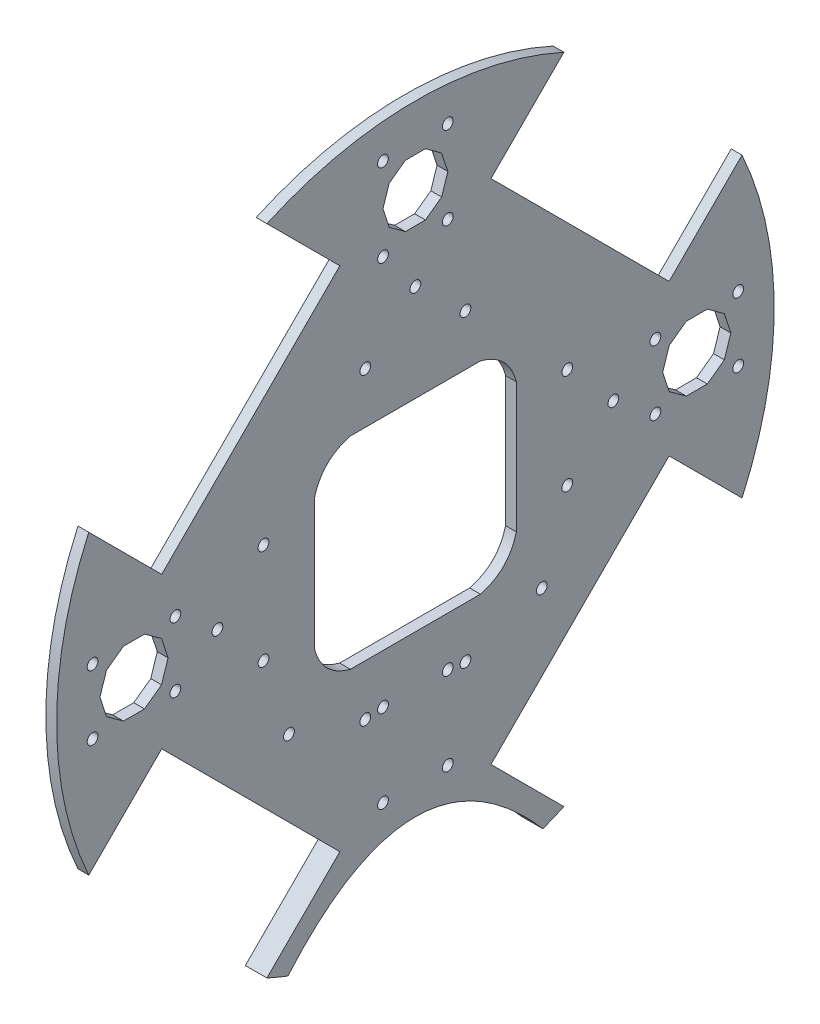
SolidWorks part; units mm, degrees
ref_plane "Front Plane" through (0, 0, 0) normal (0, 0, 1) x (1, 0, 0)
ref_plane "Top Plane" through (0, 0, 0) normal (0, 1, 0) x (1, 0, 0)
ref_plane "Right Plane" through (0, 0, 0) normal (1, 0, 0) x (0, 0, -1)
sketch "Sketch1" plane through (0, 0, 0) normal (1, 0, 0) x (0, 0, -1)
  line L7 (-70.4875, 70.4875) -> (-45.7388, 95.2363)
  line L21 (-70.4875, 70.4875) -> (-95.2363, 45.7388)
  line L23 (-95.2363, 45.7388) -> (-70.4875, 20.9901)
  line L24 (-70.4875, 20.9901) -> (-20.9901, 70.4875)
  line L25 (-20.9901, 70.4875) -> (-45.7388, 95.2363)
  line L26 (70.4875, -70.4875) -> (45.7388, -95.2363)
  line L28 (95.2363, -45.7388) -> (70.4852, -20.9878)
  line L29 (70.4852, -20.9878) -> (19.2145, -68.712)
  line L30 (19.2145, -68.712) -> (45.7388, -95.2363)
  line L31 (70.4875, -70.4875) -> (95.2363, -45.7388)
  line L32 (70.4875, 70.4875) -> (45.7388, 95.2363)
  line L33 (45.7388, 95.2363) -> (95.2363, 45.7388)
  line L34 (95.2363, 45.7388) -> (70.4852, 20.9878)
  line L35 (70.4852, 20.9878) -> (20.9855, 70.4875)
  line L36 (20.9855, 70.4875) -> (45.7388, 95.2363)
  line L37 (-70.4875, -70.4875) -> (-45.7388, -95.2363)
  line L38 (-45.7388, -95.2363) -> (-20.9901, -70.4875)
  line L39 (-20.9901, -70.4875) -> (-70.4875, -20.9901)
  line L40 (-70.4875, -20.9901) -> (-95.2363, -45.7388)
  line L41 (-95.2363, -45.7388) -> (-70.4875, -70.4875)
  circle A0 centre (0, 0) radius 99.6844
  spline S0 degree 2 poles (-29.4455, -95.2363) (0, -54.1326) (29.4455, -95.2363) knots 0 0 0 1 1 1
extrude "Boss-Extrude5" add sketch "Sketch1" along normal blind 3 contours A0 S0 L30 L29 L28 L34 L35 L36 L25 L24 L23 L40 L39 L38
sketch "Sketch5" plane through (3, 0, 0) normal (1, 0, 0) x (0, 0, -1)
  line L0 (0, 0) -> (0, -55)
  line L1 (43.3013, 0) -> (21.6506, 37.5)
  line L2 (21.6506, 37.5) -> (-21.6506, 37.5)
  line L3 (-21.6506, 37.5) -> (-43.3013, 0)
  line L4 (-43.3013, 0) -> (-21.6506, -37.5)
  line L5 (-21.6506, -37.5) -> (21.6506, -37.5)
  line L6 (21.6506, -37.5) -> (43.3013, 0)
  line L7 (0, 0) -> (55, 0)
  line L8 (55, 0) -> (0, 0)
  line L9 (0, 0) -> (0, 55)
  line L10 (0, 55) -> (0, 0)
  line L11 (0, 0) -> (-55, 0)
  circle A0 centre (0, 0) radius 37.5 construction
  circle A1 centre (0, 55) radius 1.5
  circle A2 centre (55, 0) radius 1.5
  circle A3 centre (0, -55) radius 1.5
  circle A4 centre (-55, 0) radius 1.5
extrude "Cut-Extrude2" cut sketch "Sketch5" against normal blind 3
sketch "Sketch6" plane through (3, 0, 0) normal (1, 0, 0) x (0, 0, -1)
  line L16 (41.2207, 8.9998) -> (41.2207, 8.999)
  circle A3 centre (-9.0093, 89.6878) radius 1.5
  circle A4 centre (8.9907, 89.6878) radius 1.5
  circle A5 centre (8.9907, 66.6878) radius 1.5
  circle A6 centre (-9.0093, 66.6878) radius 1.5
  circle A7 centre (-89.6848, 8.9998) radius 1.5
  circle A8 centre (-66.6848, 8.9998) radius 1.5
  circle A9 centre (-66.6848, -8.998) radius 1.5
  circle A10 centre (-89.6848, -8.998) radius 1.5
  circle A11 centre (9, -41.6844) radius 1.5
  circle A12 centre (-9, -41.6844) radius 1.5
  circle A13 centre (-9, -64.6844) radius 1.5
  circle A14 centre (9, -64.6844) radius 1.5
  circle A15 centre (66.6778, 9.0051) radius 1.5
  circle A16 centre (89.6778, 9.0051) radius 1.5
  circle A17 centre (89.6778, -8.9928) radius 1.5
  circle A18 centre (66.6778, -8.9928) radius 1.5
extrude "Cut-Extrude3" cut sketch "Sketch6" against normal blind 3 contours A7 | A8 | A10 | A9 | A4 | A3 | A6 | A5 | A15 | A16 | A17 | A18 | A11 | A12 | A13 | A14
sketch "Sketch7" plane through (3, 0, 0) normal (1, 0, 0) x (0, 0, -1)
  line L2 (21.6506, -37.5) -> (43.3013, 0)
  line L3 (43.3013, 0) -> (21.6506, 37.5)
  line L4 (21.6506, 37.5) -> (-21.6506, 37.5)
  line L5 (-21.6506, 37.5) -> (-43.3013, 0)
  line L6 (-43.3013, 0) -> (-21.6506, -37.5)
  line L7 (-21.6506, -37.5) -> (21.6506, -37.5)
  circle A0 centre (0, 0) radius 37.5 construction
extrude "Boss-Extrude7" add sketch "Sketch7" against normal blind 3 contours L2 L3 L4 L5 L6 L7
sketch "Sketch8" plane through (3, 0, 0) normal (1, 0, 0) x (0, 0, -1)
  circle A0 centre (-49.2746, 20.989) radius 1.5
  circle A1 centre (-20.99, 49.2744) radius 1.5
  circle A2 centre (20.9866, 49.2729) radius 1.5
  circle A3 centre (49.2712, 20.989) radius 1.5
  circle A4 centre (49.2692, -20.2436) radius 1.5
  circle A5 centre (19.9904, -47.4971) radius 1.5
  circle A6 centre (-20.99, -49.274) radius 1.5
  circle A7 centre (-49.2746, -20.9901) radius 1.5
extrude "Cut-Extrude4" cut sketch "Sketch8" against normal blind 3
sketch "Sketch9" plane through (3, 0, 0) normal (1, 0, 0) x (0, 0, -1)
  line L12 (32.6284, 7.0711) -> (7.0711, 32.6284)
  line L13 (-7.0711, 32.6284) -> (-32.6284, 7.0711)
  line L14 (-32.6284, -7.0711) -> (-7.0711, -32.6284)
  line L15 (7.0711, -32.6284) -> (32.6284, -7.0711)
  circle A0 centre (0, 0) radius 28.0718 construction
  arc A1 (-7.0711, -32.6284) -> (7.0711, -32.6284) centre (0, -25.5574) ccw
  arc A2 (32.6284, -7.0711) -> (32.6284, 7.0711) centre (25.5574, 0) ccw
  arc A3 (7.0711, 32.6284) -> (-7.0711, 32.6284) centre (0, 25.5574) ccw
  arc A4 (-32.6284, 7.0711) -> (-32.6284, -7.0711) centre (-25.5574, 0) ccw
  dimension "D1" = 10
extrude "Cut-Extrude5" cut sketch "Sketch9" against normal blind 3 contours L12 A3 L13 A4 L14 A1 L15 A2
sketch "Sketch10" plane through (3, 0, 0) normal (1, 0, 0) x (0, 0, -1)
  line L0 (0, 35.5574) -> (0, -35.5574) construction
  line L1 (4, 35.5574) -> (4, -35.5574)
  line L2 (-4, 35.5574) -> (-4, -35.5574)
  line L3 (-37.5957, 0) -> (35.5574, 0) construction
  line L4 (-37.5957, 4) -> (35.5574, 4)
  line L5 (-37.5957, -4) -> (35.5574, -4)
  arc A0 (7.0711, 32.6284) -> (-7.0711, 32.6284) centre (0, 25.5574) ccw construction
  arc A1 (-7.0711, -32.6284) -> (7.0711, -32.6284) centre (0, -25.5574) ccw construction
  arc A2 (4, 35.5574) -> (-4, 35.5574) centre (0, 35.5574) ccw
  arc A3 (-4, -35.5574) -> (4, -35.5574) centre (0, -35.5574) ccw
  arc A4 (32.6284, -7.0711) -> (32.6284, 7.0711) centre (25.5574, 0) ccw construction
  arc A5 (-37.5957, 4) -> (-37.5957, -4) centre (-37.5957, 0) ccw
  arc A6 (35.5574, -4) -> (35.5574, 4) centre (35.5574, 0) ccw
  point P8 (0, 0)
  point P13 (-1.0192, 0)
extrude "Boss-Extrude9" add sketch "Sketch10" against normal blind 3 contours L4 A5 L5 L2 | L5 A6 L4 L1 | L1 A2 L2 L4 | L2 A3 L1 L5 | L2 L5 L1 L4
sketch "Sketch11" plane through (3, 0, 0) normal (1, 0, 0) x (0, 0, -1)
  circle A0 centre (0, -55) radius 4.2568
extrude "Boss-Extrude10" add sketch "Sketch11" against normal blind 3
sketch "Sketch12" plane through (3, 0, 0) normal (1, 0, 0) x (0, 0, -1)
  line L0 (0, 0) -> (0, -55)
  circle A2 centre (0, -55) radius 5
extrude "Cut-Extrude6" cut sketch "Sketch12" against normal blind 2
sketch "Sketch13" plane through (3, 0, 0) normal (1, 0, 0) x (0, 0, -1)
  line L0 (0, 0) -> (0, -55)
  circle A0 centre (0, -55) radius 1.5
extrude "Cut-Extrude10" cut sketch "Sketch13" against normal blind 10
sketch "Sketch14" plane through (3, 0, 0) normal (1, 0, 0) x (0, 0, -1)
  line L0 (-4, 34.7225) -> (4, 34.7225)
  line L1 (4, 34.7225) -> (4, 4)
  line L2 (4, 4) -> (34.7225, 4)
  line L3 (34.7225, 4) -> (34.7225, -4)
  line L4 (34.7225, -4) -> (4, -4)
  line L5 (4, -4) -> (4, -34.7225)
  line L6 (4, -34.7225) -> (-4, -34.7225)
  line L7 (-4, -34.7225) -> (-4, -4)
  line L8 (-4, -4) -> (-34.7225, -4)
  line L9 (-34.7225, -4) -> (-34.7225, 4)
  line L10 (-34.7225, 4) -> (-4, 4)
  line L11 (-4, 4) -> (-4, 34.7225)
extrude "Cut-Extrude11" cut sketch "Sketch14" against normal blind 10 contours L11 L0 L1 L2 L3 L4 L5 L6 L7 L8 L9 L10
sketch "Sketch15" plane through (3, 0, 0) normal (1, 0, 0) x (0, 0, -1)
  line L0 (-29.4455, -95.2363) -> (-35.4195, -93.1796)
  line L1 (-20.9901, -70.4875) -> (20.9901, -70.4875)
  line L2 (19.2145, -68.712) -> (41.2512, -90.7487) construction
  line L3 (90.7487, -41.2512) -> (70.4852, -20.9878)
  line L4 (70.4852, -20.9878) -> (20.9901, -70.4875)
  line L5 (20.9901, -70.4875) -> (19.2145, -68.712)
  line L6 (19.2145, -68.712) -> (70.4852, -20.9878)
  arc A0 (-41.2512, -90.7487) -> (-29.4455, -95.2363) centre (0, 0) ccw construction
extrude "Boss-Extrude11" add sketch "Sketch15" against normal blind 3 contours L6 L5 L4
sketch "Sketch16" plane through (3, 0, 0) normal (1, 0, 0) x (0, 0, -1)
  line L0 (-20.9901, -70.4875) -> (20.9901, -70.4875)
  line L1 (0, -70.4875) -> (0, -74.6844)
  line L2 (-35.4195, -93.1796) -> (-29.4455, -95.2363)
  line L3 (29.4455, -95.2363) -> (35.4195, -93.1796)
  line L4 (-35.4195, -93.1796) -> (-36.1047, -94.1619)
  line L5 (-36.1047, -94.1619) -> (-29.2458, -96.6155)
  line L6 (-29.2458, -96.6155) -> (-29.4455, -95.2363)
  line L7 (29.4455, -95.2363) -> (26.5031, -98.1787)
  line L8 (26.5031, -98.1787) -> (37.9172, -96.526)
  line L9 (37.9172, -96.526) -> (35.4195, -93.1796)
  arc A0 (-41.2512, -90.7487) -> (-29.4455, -95.2363) centre (0, 0) ccw construction
  arc A1 (29.4455, -95.2363) -> (41.2512, -90.7487) centre (0, 0) ccw construction
  parabola Q0 (-29.4455, -95.2363) -> (29.4455, -95.2363) focus (0, -85.2314) apex (0, -74.6844) construction
  parabola Q1 (-29.4455, -95.2363) -> (29.4455, -95.2363) focus (0, -85.2314) apex (0, -74.6844) construction
  spline S0 degree 2 poles (-35.4195, -93.1796) (0, -51.9923) (35.4195, -93.1796) knots 0 0 0 1 1 1
  spline S1 degree 2 poles (-29.4455, -95.2363) (0, -54.1326) (29.4455, -95.2363) knots 0 0 0 1 1 1
extrude "Cut-Extrude13" cut sketch "Sketch16" against normal blind 3 contours L8 L9 L3 L7 | L1 S1 L3 S0 | L2 S1 L1 S0 | L5 L6 L2 L4
sketch "Sketch17" plane through (3, 0, 0) normal (1, 0, 0) x (0, 0, -1)
  line L0 (-41.2512, -90.7487) -> (-20.9901, -70.4875)
  line L1 (-20.9901, -70.4875) -> (20.9901, -70.4875)
  line L2 (20.9901, -70.4875) -> (41.2512, -90.7487)
  line L3 (41.2512, -90.7487) -> (35.4195, -93.1796)
  line L4 (-41.2512, -90.7487) -> (-35.4195, -93.1796)
  parabola Q0 (-35.4195, -93.1796) -> (35.4195, -93.1796) focus (0, -87.8157) apex (0, -72.586) construction
  spline S0 degree 2 poles (-35.4195, -93.1796) (0, -51.9923) (35.4195, -93.1796) knots 0 0 0 1 1 1
extrude "Boss-Extrude13" add sketch "Sketch17" against normal blind 6 contours S0 L3 L2 L1 L0 L4
sketch "Sketch19" plane through (-3, 0, 0) normal (-1, 0, 0) x (0, 0, 1)
  line L0 (-49.2692, -20.2436) -> (-52.8047, -23.7791)
  line L1 (-49.2712, 20.989) -> (-52.8067, 24.5245)
  line L2 (-19.9904, -47.4971) -> (-23.526, -51.0326)
  line L3 (20.99, -49.274) -> (24.5255, -52.8095)
  line L4 (49.2746, -20.9901) -> (52.8102, -24.5256)
  line L5 (49.2746, 20.989) -> (52.8102, 24.5245)
  line L6 (20.99, 49.2744) -> (24.5255, 52.8099)
  line L7 (-20.9866, 49.2729) -> (-24.5236, 52.8099)
  circle A0 centre (-52.8067, 24.5245) radius 1.5
  circle A1 centre (-24.5236, 52.8099) radius 1.5
  circle A2 centre (24.5255, 52.8099) radius 1.5
  circle A3 centre (52.788, 24.5204) radius 1.5
  circle A4 centre (52.8102, -24.5256) radius 1.5
  circle A5 centre (24.5255, -52.8095) radius 1.5
  circle A6 centre (-23.526, -51.0326) radius 1.5
  circle A7 centre (-52.8047, -23.7791) radius 1.5
  circle A8 centre (-49.2692, -20.2436) radius 1.5
  circle A9 centre (-49.2712, 20.989) radius 1.5
  circle A10 centre (-20.9866, 49.2729) radius 1.5
  circle A11 centre (20.99, 49.2744) radius 1.5
  circle A12 centre (49.2746, 20.989) radius 1.5
  circle A13 centre (49.2746, -20.9901) radius 2.1805
  circle A14 centre (20.99, -49.274) radius 1.5
  circle A15 centre (-19.9904, -47.4971) radius 2.0047
extrude "Cut-Extrude14" cut sketch "Sketch19" against normal blind 6
sketch "Sketch20" plane through (0, 0, 0) normal (-1, 0, 0) x (0, 0, 1)
  circle A0 centre (-49.2692, -20.2436) radius 1.5
  circle A1 centre (-19.9904, -47.4971) radius 1.5
  circle A2 centre (-49.2712, 20.989) radius 1.5
  circle A3 centre (-20.9866, 49.2729) radius 1.804
  circle A4 centre (20.99, 49.2744) radius 1.5772
  circle A5 centre (49.2746, 20.989) radius 1.5
  circle A6 centre (49.2746, -20.9901) radius 1.5
  circle A7 centre (20.99, -49.274) radius 1.851
extrude "Boss-Extrude15" add sketch "Sketch20" against normal blind 3 contours A3 | A1 | A7 | A6 | A5 | A4 | A2 | A0
sketch "Sketch21" plane through (0, 0, 0) normal (-1, 0, 0) x (0, 0, 1)
  line L69 (87.648, 0.0009) -> (85.8407, 5.5632)
  line L70 (85.8407, 5.5632) -> (81.1091, 9.0009)
  line L71 (81.1091, 9.0009) -> (75.2606, 9.0009)
  line L72 (75.2606, 9.0009) -> (70.529, 5.5632)
  line L73 (70.529, 5.5632) -> (68.7217, 0.0009)
  line L74 (68.7217, 0.0009) -> (70.529, -5.5614)
  line L75 (70.529, -5.5614) -> (75.2606, -8.9991)
  line L76 (75.2606, -8.9991) -> (81.1091, -8.9991)
  line L77 (81.1091, -8.9991) -> (85.8407, -5.5614)
  line L78 (85.8407, -5.5614) -> (87.648, 0.0009)
  line L80 (-68.7147, 0.0061) -> (-70.522, 5.5684)
  line L81 (-70.522, 5.5684) -> (-75.2536, 9.0061)
  line L82 (-75.2536, 9.0061) -> (-81.1021, 9.0061)
  line L83 (-81.1021, 9.0061) -> (-85.8337, 5.5684)
  line L84 (-85.8337, 5.5684) -> (-87.641, 0.0061)
  line L85 (-87.641, 0.0061) -> (-85.8337, -5.5562)
  line L86 (-85.8337, -5.5562) -> (-81.1021, -8.9939)
  line L87 (-81.1021, -8.9939) -> (-75.2536, -8.9939)
  line L88 (-75.2536, -8.9939) -> (-70.522, -5.5562)
  line L89 (-70.522, -5.5562) -> (-68.7147, 0.0061)
  line L90 (9.0093, 78.1878) -> (7.2886, 83.4834)
  line L91 (7.2886, 83.4834) -> (2.784, 86.7562)
  line L92 (2.784, 86.7562) -> (-2.784, 86.7562)
  line L93 (-2.784, 86.7562) -> (-7.2886, 83.4834)
  line L94 (-7.2886, 83.4834) -> (-9.0093, 78.1878)
  line L95 (-9.0093, 78.1878) -> (-7.2886, 72.8923)
  line L96 (-7.2886, 72.8923) -> (-2.784, 69.6195)
  line L97 (-2.784, 69.6195) -> (2.784, 69.6195)
  line L98 (2.784, 69.6195) -> (7.2886, 72.8923)
  line L99 (7.2886, 72.8923) -> (9.0093, 78.1878)
  circle A0 centre (-78.1778, 0.0061) radius 9 construction
  circle A9 centre (78.1848, 0.0009) radius 9 construction
  circle A14 centre (0, 78.1878) radius 8.5683 construction
extrude "Cut-Extrude15" cut sketch "Sketch21" against normal blind 3 contours L69 L70 L71 L72 L73 L74 L75 L76 L77 L78 | L90 L91 L92 L93 L94 L95 L96 L97 L98 L99 | L80 L81 L82 L83 L84 L85 L86 L87 L88 L89
sketch "Sketch23" plane through (0, 0, 0) normal (-1, 0, 0) x (0, 0, 1)
  line L2 (20.9901, -70.4875) -> (70.4875, -20.9901) construction
  line L3 (59.8811, -31.5965) -> (31.5967, -59.8809)
  line L5 (26.4902, -51.1933) -> (51.7565, -25.5932) construction
  line L11 (23.1851, -47.9313) -> (48.4514, -22.3312)
  line L12 (29.7953, -54.4552) -> (55.0616, -28.8552)
  circle A2 centre (52.8102, -24.5256) radius 1.5 construction
  arc A3 (23.1851, -47.9313) -> (29.7953, -54.4552) centre (26.4902, -51.1933) ccw
  arc A4 (55.0616, -28.8552) -> (48.4514, -22.3312) centre (51.7565, -25.5932) ccw
  point P10 (39.1233, -38.3932)
extrude "Boss-Extrude17" add sketch "Sketch23" against normal blind 3
sketch "Sketch24" plane through (0, 0, 0) normal (-1, 0, 0) x (0, 0, 1)
  line L0 (-52.8047, -25.2791) -> (-24.5592, -52.12) construction
  line L1 (-49.933, -22.2571) -> (-21.6875, -49.0979)
  line L2 (-55.6765, -28.3012) -> (-27.431, -55.142)
  circle A0 centre (-52.8047, -23.7791) radius 1.5 construction
  circle A1 centre (-23.526, -51.0326) radius 1.5 construction
  arc A2 (-49.933, -22.2571) -> (-55.6765, -28.3012) centre (-52.8047, -25.2791) ccw
  arc A3 (-27.431, -55.142) -> (-21.6875, -49.0979) centre (-24.5592, -52.12) ccw
  point P6 (-38.682, -38.6996)
extrude "Boss-Extrude18" add sketch "Sketch24" against normal blind 3
sketch "Sketch25" plane through (0, 0, 0) normal (-1, 0, 0) x (0, 0, 1)
  line L0 (-51.3067, 24.5245) -> (-23.4749, 51.7374) construction
  line L1 (-53.9248, 27.2021) -> (-26.093, 54.415)
  line L2 (-48.6887, 21.8469) -> (-20.8569, 49.0598)
  circle A0 centre (-52.8067, 24.5245) radius 1.5 construction
  circle A1 centre (-24.5236, 52.8099) radius 1.5 construction
  arc A2 (-53.9248, 27.2021) -> (-48.6887, 21.8469) centre (-51.3067, 24.5245) ccw
  arc A3 (-20.8569, 49.0598) -> (-26.093, 54.415) centre (-23.4749, 51.7374) ccw
  point P6 (-37.3908, 38.1309)
extrude "Boss-Extrude19" add sketch "Sketch25" against normal blind 3
sketch "Sketch26" plane through (0, 0, 0) normal (-1, 0, 0) x (0, 0, 1)
  line L0 (24.5255, 51.3099) -> (51.288, 24.5204) construction
  line L1 (27.5686, 54.3499) -> (54.3311, 27.5604)
  line L2 (21.4825, 48.2699) -> (48.245, 21.4804)
  circle A0 centre (24.5255, 52.8099) radius 1.5 construction
  circle A1 centre (52.788, 24.5204) radius 1.5 construction
  arc A2 (27.5686, 54.3499) -> (21.4825, 48.2699) centre (24.5255, 51.3099) ccw
  arc A3 (48.245, 21.4804) -> (54.3311, 27.5604) centre (51.288, 24.5204) ccw
  point P6 (37.9068, 37.9151)
extrude "Boss-Extrude20" add sketch "Sketch26" against normal blind 3
sketch "Sketch27" plane through (0, 0, 0) normal (-1, 0, 0) x (0, 0, 1)
  circle A0 centre (0, 0) radius 37.8609
extrude "Boss-Extrude21" add sketch "Sketch27" against normal blind 3
sketch "Sketch28" plane through (0, 0, 0) normal (-1, 0, 0) x (0, 0, 1)
  line L0 (-70.4852, 20.9878) -> (-59.8786, 31.5944)
  line L1 (-70.4852, 20.9878) -> (-20.9855, 70.4875) construction
  line L2 (-59.8786, 31.5944) -> (-20.9855, 70.4875)
  line L3 (-20.9855, 70.4875) -> (-31.5921, 59.8809)
  line L7 (-59.8786, 31.5944) -> (-31.5921, 59.8809)
  line L8 (-70.4852, -20.9878) -> (-59.8791, -31.5949)
  line L9 (-70.4852, -20.9878) -> (-20.9901, -70.4875) construction
  line L13 (20.9901, -70.4875) -> (31.5967, -59.8809)
  line L14 (20.9901, -70.4875) -> (70.4875, -20.9901) construction
  line L18 (59.8819, -31.5957) -> (70.4875, -20.9901)
  line L19 (20.9901, 70.4875) -> (31.5967, 59.8809)
  line L20 (70.4875, 20.9901) -> (20.9901, 70.4875) construction
  line L24 (59.8819, 31.5957) -> (70.4875, 20.9901)
  circle A0 centre (-42.201, 13.9167) radius 1.5
  circle A1 centre (-13.9144, 42.2033) radius 1.5
  circle A2 centre (13.919, 42.2033) radius 1.5
  circle A3 centre (42.2042, 13.918) radius 1.5
  circle A4 centre (42.2042, -13.918) radius 1.5
  circle A5 centre (13.919, -42.2033) radius 1.5
  circle A6 centre (-13.9144, -42.2068) radius 1.5
  circle A7 centre (-42.2006, -13.918) radius 1.5
extrude "Cut-Extrude16" cut sketch "Sketch28" against normal blind 3 contours A0 | A7 | A6 | A4 | A3 | A2 | A1 | A5
sketch "Sketch29" plane through (0, 0, 0) normal (-1, 0, 0) x (0, 0, 1)
  line L11 (-28.0575, -28.0624) -> (28.0616, -28.0624)
  line L12 (-28.0575, -28.0624) -> (-28.0575, 28.0606)
  line L13 (-28.0575, 28.0606) -> (28.0616, 28.0606)
  line L14 (28.0616, -28.0624) -> (28.0616, 28.0606)
  line L15 (-28.0575, 28.0606) -> (-28.0575, 18.0606)
  line L16 (-28.0575, 18.0606) -> (-18.0575, 28.0606)
  line L17 (-18.0575, 28.0606) -> (-28.0575, 28.0606)
  line L19 (-28.0575, 28.0606) -> (-24.522, 24.5251)
  line L22 (28.0616, 28.0606) -> (24.5261, 24.5251)
  line L25 (28.0616, 28.0606) -> (18.0616, 28.0606)
  line L26 (18.0616, 28.0606) -> (28.0616, 18.0606)
  line L30 (-28.0575, -28.0624) -> (-28.0575, -18.0624)
  line L31 (-28.0575, -28.0624) -> (-18.0575, -28.0624)
  line L34 (-28.0575, -28.0624) -> (-24.522, -24.5269)
  line L37 (28.0616, -28.0624) -> (18.0616, -28.0624)
  line L38 (18.0616, -28.0624) -> (28.0616, -18.0624)
  line L40 (28.0616, -28.0624) -> (24.5261, -24.5269)
  spline S0 degree 2 poles (-28.0575, 18.0606) (-25.9865, 25.9896) (-18.0575, 28.0606) knots 0 0 0 1 1 1
  spline S1 degree 2 poles (18.0616, 28.0606) (25.9905, 25.9896) (28.0616, 18.0606) knots 0 0 0 1 1 1
  spline S2 degree 2 poles (-28.0575, -18.0624) (-25.9865, -25.9914) (-18.0575, -28.0624) knots 0 0 0 1 1 1
  spline S3 degree 2 poles (18.0616, -28.0624) (25.9905, -25.9914) (28.0616, -18.0624) knots 0 0 0 1 1 1
extrude "Cut-Extrude19" cut sketch "Sketch29" against normal blind 3 contours L12 S2 L11 L38 L14 L26 L13 L16 | S0 L16 | S1 L26
sketch "Sketch32" plane through (0, 0, 0) normal (-1, 0, 0) x (0, 0, 1)
  line L0 (-20.9855, 70.4875) -> (-19.5713, 71.9017)
  line L1 (-71.8994, -19.5735) -> (-90.1654, -37.8378)
  line L2 (71.8994, 19.5738) -> (90.1654, 37.8414)
  line L3 (-19.5713, 71.9017) -> (-37.8358, 90.1663)
  line L4 (71.8994, -19.5735) -> (90.1654, -37.8378)
  line L5 (19.5713, 71.9017) -> (37.8358, 90.1663)
  line L6 (-71.8994, 19.5738) -> (-90.1654, 37.8414)
  line L7 (-90.1654, 37.8414) -> (-81.0324, 28.7076)
  spline S0 degree 2 poles (-90.1654, -37.8378) (-102.2446, -7.4915) (-71.8994, -19.5735) knots 0 0 0 1 1 1
  spline S1 degree 2 poles (90.1654, -37.8378) (102.2446, -7.4915) (71.8994, -19.5735) knots 0 0 0 1 1 1
  spline S2 degree 2 poles (-90.1654, 37.8414) (-102.2446, 7.4973) (-71.8994, 19.5738) knots 0 0 0 1 1 1
  spline S3 degree 2 poles (90.1654, 37.8414) (102.2446, 7.4973) (71.8994, 19.5738) knots 0 0 0 1 1 1
  spline S4 degree 2 poles (-37.8358, 90.1663) (-7.4904, 102.2472) (-19.5713, 71.9017) knots 0 0 0 1 1 1
  spline S5 degree 2 poles (37.8358, 90.1663) (7.4904, 102.2472) (19.5713, 71.9017) knots 0 0 0 1 1 1
extrude "Cut-Extrude21" cut sketch "Sketch32" along normal blind 1 and the other way blind 2 contours L6 S2 | S4 L3 | L5 S5 | S3 L2 | L4 S1 | S0 L1
sketch "Sketch33" plane through (1, 0, 0) normal (1, 0, 0) x (0, 0, -1)
  circle A0 centre (0, -55) radius 5
extrude "Boss-Extrude22" add sketch "Sketch33" along normal blind 2 and the other way blind 1
sketch "Sketch34" plane through (0, 0, 0) normal (-1, 0, 0) x (0, 0, 1)
  circle A0 centre (-35.131, -35.131) radius 1.5
  circle A1 centre (35.1322, -35.1322) radius 1.5
extrude "Cut-Extrude23" cut sketch "Sketch34" along normal blind 14 and the other way blind 25
